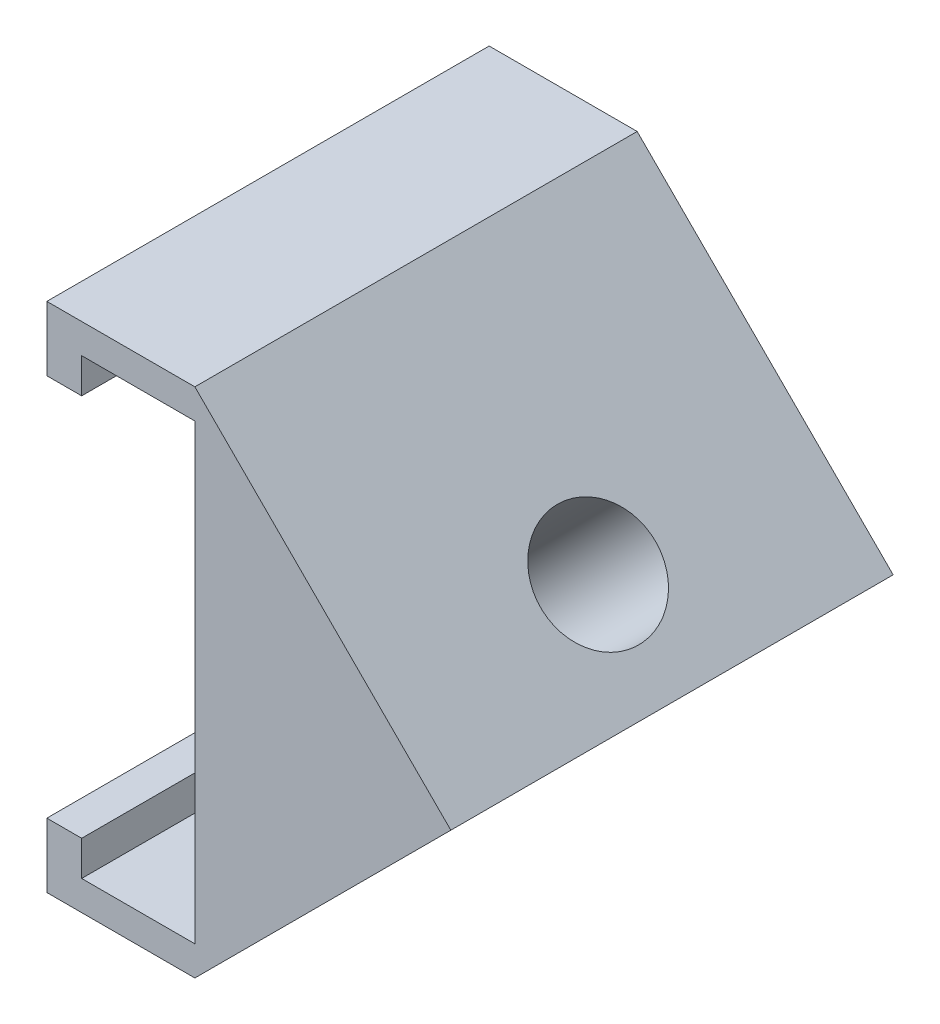
SolidWorks part; units mm, degrees
ref_plane "Front Plane" through (0, 0, 0) normal (0, 0, 1) x (1, 0, 0)
ref_plane "Top Plane" through (0, 0, 0) normal (0, 1, 0) x (1, 0, 0)
ref_plane "Right Plane" through (0, 0, 0) normal (1, 0, 0) x (0, 0, -1)
sketch "Sketch1" plane through (0, 0, 0) normal (0, 0, 1) x (1, 0, 0)
  line L0 (-7.35, 7.35) -> (0, 0)
  line L1 (-11.6, 7.35) -> (-7.35, 7.35)
  line L2 (-11.6, 7.35) -> (-11.6, 6.5)
  line L3 (-11.6, -7.35) -> (-7.35, -7.35)
  line L7 (0, 0) -> (-7.35, -7.35)
  line L12 (-7.35, 6.5) -> (-7.35, -6.5)
  line L13 (-11.6, -6.5) -> (-11.6, -7.35)
  line L14 (0, 0) -> (-7.35, 0) construction
  line L16 (-11.6, -6.5) -> (-11.6, -5.5)
  line L17 (-11.6, -5.5) -> (-10.6, -5.5)
  line L18 (-10.6, -6.5) -> (-10.6, -5.5)
  line L19 (-11.6, 5.5) -> (-10.6, 5.5)
  line L20 (-10.6, 6.5) -> (-10.6, 5.5)
  line L22 (-11.6, 6.5) -> (-11.6, 5.5)
  line L23 (-10.6, 6.5) -> (-7.35, 6.5)
  line L24 (-10.6, -6.5) -> (-7.35, -6.5)
  line L25 (-7.35, 7.35) -> (-7.35, -7.35) construction
  dimension "D1" = 14.7
  dimension "D2" = 4.25
  dimension "D3" = 4.25
  dimension "D4" = 13
  dimension "D5" = 3.25
  dimension "D6" = 1
  dimension "D7" = 225
extrude "Boss-Extrude1" add sketch "Sketch1" along normal blind 12.7
sketch "Sketch7" plane through (0, 0, 0) normal (0.7071, 0.7071, 0) x (0, 0, -1)
  line L0 (-12.7, 0) -> (0, 0) construction
  line L1 (-6.35, 10.3945) -> (-6.35, 0) construction
  line L2 (-12.7, 10.3945) -> (0, 10.3945) construction
  circle A0 centre (-6.35, 3) radius 1.65
  point P8 (0, 0)
  dimension "D1" = 3.3
  dimension "D2" = 3
extrude "Cut-Extrude2" cut sketch "Sketch7" against normal blind 5
